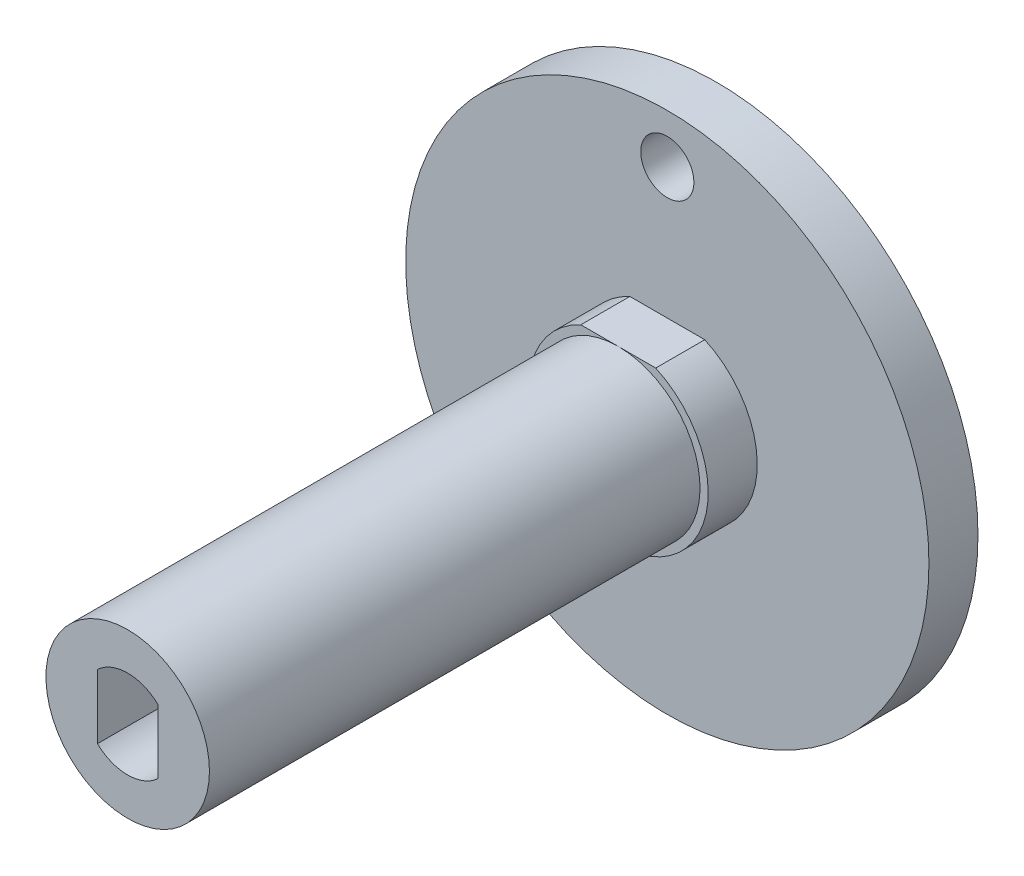
SolidWorks part; units mm, degrees
material "ABS"
ref_plane "Front Plane" through (0, 0, 0) normal (0, 0, 1) x (1, 0, 0)
ref_plane "Top Plane" through (0, 0, 0) normal (0, 1, 0) x (1, 0, 0)
ref_plane "Right Plane" through (0, 0, 0) normal (1, 0, 0) x (0, 0, -1)
sketch "Sketch1" plane through (0, 0, 0) normal (0, 0, 1) x (1, 0, 0)
  line L0 (0, 0) -> (0, 13) construction
  line L1 (0, 16) -> (26.9161, 16) construction
  circle A1 centre (0, 0) radius 16
  circle A2 centre (0, 13) radius 1.625
  dimension "D1" = 32
  dimension "D2" = 3
  dimension "D3" = 3.25
extrude "Boss-Extrude1" add sketch "Sketch1" along normal blind 3
sketch "Sketch2" plane through (0, 0, 3) normal (0, 0, 1) x (1, 0, 0)
  line L0 (-2.2913, 5) -> (2.2913, 5)
  arc A0 (-2.2913, 5) -> (2.2913, 5) centre (0, 0) ccw
  dimension "D1" = 11
  dimension "D2" = 5
extrude "Boss-Extrude2" add sketch "Sketch2" along normal blind 3
sketch "Sketch3" plane through (0, 0, 6) normal (0, 0, 1) x (1, 0, 0)
  circle A0 centre (0, 0) radius 5
  dimension "D1" = 10
extrude "Boss-Extrude3" add sketch "Sketch3" along normal blind 30
sketch "Sketch4" plane through (0, 0, 36) normal (0, 0, 1) x (1, 0, 0)
  line L2 (1.85, -1.9666) -> (1.85, 1.9666)
  line L4 (-1.85, -1.9666) -> (-1.85, 1.9666)
  line L5 (1.3174, -2.3568) -> (-1.3174, 2.3568) construction
  line L6 (1.3174, 2.3568) -> (-1.3174, -2.3568) construction
  arc A0 (1.85, 1.9666) -> (-1.85, 1.9666) centre (0, 0) ccw
  arc A1 (-1.85, -1.9666) -> (1.85, -1.9666) centre (0, 0) ccw
  dimension "D1" = 5.4
extrude "Cut-Extrude1" cut sketch "Sketch4" against normal blind 8
